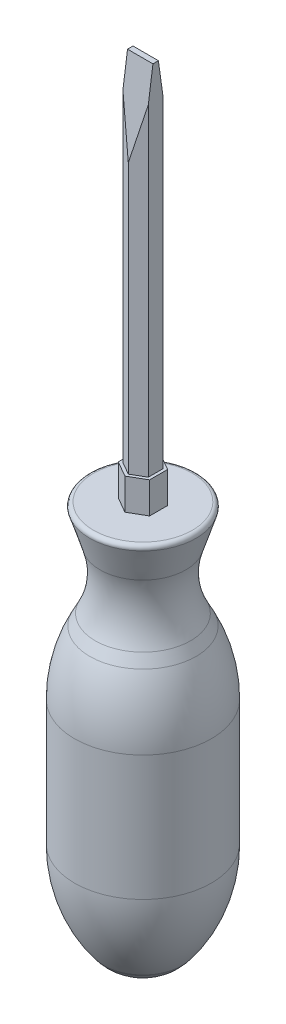
SolidWorks part; units mm, degrees
material "V2a"
ref_plane "Vorne" through (0, 0, 0) normal (0, 0, 1) x (1, 0, 0)
ref_plane "Oben" through (0, 0, 0) normal (0, 1, 0) x (1, 0, 0)
ref_plane "Rechts" through (0, 0, 0) normal (1, 0, 0) x (0, 0, -1)
sketch "Skizze1" plane through (0, 0, 0) normal (0, 0, 1) x (1, 0, 0)
  line L0 (0, 79.6262) -> (0, -138.7073) construction
  line L1 (-9.7044, -98.1339) -> (-9.932, -97.8408)
  line L2 (-17.5, -75.7587) -> (-17.5, -43.7697)
  line L3 (-13.603, -27.4787) -> (-12.1987, -24.7113)
  line L4 (-10.9676, -9.6204) -> (-13.603, -1.302)
  line L5 (-12.6497, 0) -> (0, 0)
  line L6 (-1.8066, -102) -> (0, -102)
  line L7 (-22.099, 0) -> (34.9854, 0) construction
  line L8 (0, 0) -> (0, -102)
  arc A0 (-9.7044, -98.1339) -> (-1.8066, -102) centre (-1.8066, -92) ccw
  arc A1 (-9.932, -97.8408) -> (-17.5, -75.7587) centre (18.5, -75.7587) cw
  arc A2 (-17.5, -43.7697) -> (-13.603, -27.4787) centre (18.5, -43.7697) cw
  arc A3 (-12.1987, -24.7113) -> (-10.9676, -9.6204) centre (-30.0337, -15.6608) ccw
  arc A4 (-13.603, -1.302) -> (-12.6497, 0) centre (-12.6497, -1) cw
  dimension "D1" = 10
  dimension "D2" = 36
  dimension "D3" = 36
  dimension "D4" = 20
  dimension "D5" = 1
  dimension "D6" = 102
  dimension "D7" = 35
  dimension "D8" = 18.5
  dimension "D9" = 1.8066
  dimension "D10" = 9.7044
  dimension "D11" = 10.9676
  dimension "D12" = 12.1987
  dimension "D13" = 12.6497
  dimension "D14" = 13.603
revolve "Rotation3" add sketch "Skizze1" angle 360 about L0
sketch "Skizze2" plane through (0, 0, 0) normal (0, 1, 0) x (1, 0, 0)
  line L0 (0, -7.1023) -> (0, 7.4391) construction
  line L1 (-4, -2.3094) -> (0, -4.6188)
  line L2 (0, -4.6188) -> (4, -2.3094)
  line L3 (4, -2.3094) -> (4, 2.3094)
  line L4 (4, 2.3094) -> (0, 4.6188)
  line L5 (0, 4.6188) -> (-4, 2.3094)
  line L6 (-4, 2.3094) -> (-4, -2.3094)
  circle A0 centre (0, 0) radius 4 construction
  dimension "D1" = 8
extrude "Aufsatz-Linear austragen1" add sketch "Skizze2" along normal blind 8
sketch "Skizze3" plane through (0, 8, 0) normal (0, 1, 0) x (1, 0, 0)
  line L0 (0, -4.6188) -> (0, 4.6188) construction
  line L1 (-3.25, -1.8764) -> (0, -3.7528)
  line L2 (0, -3.7528) -> (3.25, -1.8764)
  line L3 (3.25, -1.8764) -> (3.25, 1.8764)
  line L4 (3.25, 1.8764) -> (0, 3.7528)
  line L5 (0, 3.7528) -> (-3.25, 1.8764)
  line L6 (-3.25, 1.8764) -> (-3.25, -1.8764)
  circle A0 centre (0, 0) radius 3.25 construction
  dimension "D1" = 6.5
extrude "Aufsatz-Linear austragen2" add sketch "Skizze3" along normal blind 91
sketch "Skizze4" plane through (0, 0, 0) normal (1, 0, 0) x (0, 0, -1)
  line L0 (-0.7, 99) -> (-3.7528, 77)
  line L1 (-1.8764, 99) -> (1.8764, 99) construction
  line L2 (-3.7528, 99) -> (-3.7528, 8) construction
  line L3 (0.7, 99) -> (3.7528, 77)
  line L4 (3.7528, 99) -> (3.7528, 8) construction
  line L5 (-0.7, 99) -> (0.7, 99)
  line L6 (0, 107.1728) -> (0, 70.2013) construction
  line L7 (-0.7, 99) -> (-3.7528, 99)
  line L8 (-3.7528, 99) -> (-3.7528, 77)
  line L9 (0.7, 99) -> (3.7528, 99)
  line L10 (3.7528, 99) -> (3.7528, 77)
  dimension "D1" = 1.4
  dimension "D2" = 22
extrude "Schnitt-Linear austragen1" cut sketch "Skizze4" against normal through all both and the other way through all contours L9 L10 L3 | L0 L8 L7
